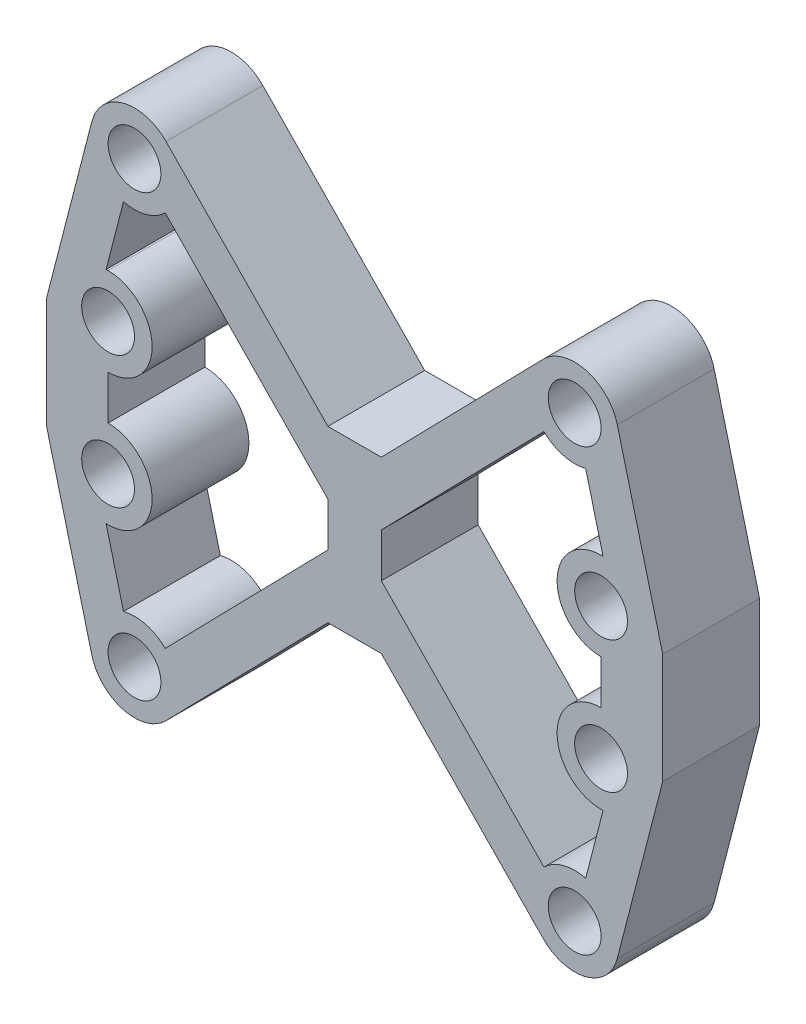
SolidWorks part; units mm, degrees
ref_plane "Front Plane" through (0, 0, 0) normal (0, 0, 1) x (1, 0, 0)
ref_plane "Top Plane" through (0, 0, 0) normal (0, 1, 0) x (1, 0, 0)
ref_plane "Right Plane" through (0, 0, 0) normal (1, 0, 0) x (0, 0, -1)
sketch "Sketch1" plane through (0, 0, 0) normal (0, 0, 1) x (1, 0, 0)
  line L0 (-5.2387, -9.525) -> (-13.6031, -18.0929)
  line L1 (-5.2387, 9.525) -> (5.2387, 9.525)
  line L2 (-22.225, 3.9688) -> (-22.225, -3.9688)
  line L3 (-5.2387, -9.525) -> (5.2387, -9.525)
  line L5 (-5.2387, 9.525) -> (-13.6031, 18.0929)
  line L8 (-22.225, 3.9688) -> (-18.9494, 16.668)
  line L9 (5.2387, -9.525) -> (13.6031, -18.0929)
  line L10 (-22.225, -3.9688) -> (-18.9494, -16.668)
  line L13 (5.2387, 9.525) -> (13.6031, 18.0929)
  line L14 (18.9494, 16.668) -> (22.225, 3.9688)
  line L15 (22.225, 3.9688) -> (22.225, -3.9687)
  line L16 (22.225, -3.9687) -> (18.9494, -16.668)
  arc A0 (-18.9494, -16.668) -> (-13.6031, -18.0929) centre (-15.875, -15.875) ccw
  arc A1 (-13.6031, 18.0929) -> (-18.9494, 16.668) centre (-15.875, 15.875) ccw
  arc A2 (13.6031, -18.0929) -> (18.9494, -16.668) centre (15.875, -15.875) ccw
  arc A3 (18.9494, 16.668) -> (13.6031, 18.0929) centre (15.875, 15.875) ccw
  point P2 (-22.225, 0)
  point P8 (0, -9.525)
  point P23 (0, 9.525)
  dimension "D1" = 6.35
  dimension "D2" = 44.45
  dimension "D3" = 15.875
  dimension "D4" = 10.4775
  dimension "D5" = 9.525
  dimension "D6" = 9.525
  dimension "D7" = 15.875
  dimension "D8" = 7.9375
extrude "Boss-Extrude1" add sketch "Sketch1" along normal blind 6.985
sketch "Sketch3" plane through (0, 0, 6.985) normal (0, 0, 1) x (1, 0, 0)
  line L1 (-18.9494, 16.668) -> (-22.225, 3.9688) construction
  line L2 (-22.225, 3.9688) -> (-22.225, -3.9688) construction
  line L3 (-1.9269, 6.1326) -> (1.9269, 6.1326)
  line L4 (-17.9224, 7.9375) -> (-16.668, 12.8006)
  line L9 (0, 9.525) -> (0, -9.525) construction
  line L11 (5.2387, 9.525) -> (-5.2387, 9.525) construction
  line L12 (-5.2387, -9.525) -> (5.2387, -9.525) construction
  line L13 (-22.225, 0) -> (22.225, 0) construction
  line L14 (22.225, -3.9687) -> (22.225, 3.9688) construction
  line L47 (-17.9224, 7.9375) -> (-17.78, 7.9375)
  line L57 (-1.9269, 1.5875) -> (-1.9269, -1.5875)
  line L58 (-17.78, 1.5875) -> (-17.78, -1.5875)
  line L60 (-17.9224, -7.9375) -> (-17.78, -7.9375)
  line L62 (-17.9224, -7.9375) -> (-16.668, -12.8006)
  line L63 (-13.6571, 13.6031) -> (-1.9269, 1.5875)
  line L64 (-13.6571, -13.6031) -> (-1.9269, -1.5875)
  line L65 (-5.2387, 9.525) -> (-13.6031, 18.0929) construction
  line L66 (17.9224, -7.9375) -> (16.668, -12.8006)
  line L67 (17.9224, -7.9375) -> (17.78, -7.9375)
  line L68 (17.78, 1.5875) -> (17.78, -1.5875)
  line L69 (17.9224, 7.9375) -> (17.78, 7.9375)
  line L70 (17.9224, 7.9375) -> (16.668, 12.8006)
  line L71 (13.6571, 13.6031) -> (1.9269, 1.5875)
  line L72 (1.9269, 1.5875) -> (1.9269, -1.5875)
  line L73 (13.6571, -13.6031) -> (1.9269, -1.5875)
  line L74 (-5.2387, 9.525) -> (-1.9269, 6.1326)
  line L75 (-5.2387, 9.525) -> (5.2387, 9.525)
  line L80 (5.2387, 9.525) -> (1.9269, 6.1326)
  line L81 (-5.2387, -9.525) -> (5.2387, -9.525)
  line L82 (-5.2387, -9.525) -> (-1.9269, -6.1326)
  line L83 (-1.9269, -6.1326) -> (1.9269, -6.1326)
  line L84 (5.2387, -9.525) -> (1.9269, -6.1326)
  circle A0 centre (-15.875, 15.875) radius 1.905
  arc A8 (-16.668, 12.8006) -> (-13.6571, 13.6031) centre (-15.875, 15.875) ccw
  arc A13 (-13.6031, 18.0929) -> (-18.9494, 16.668) centre (-15.875, 15.875) ccw construction
  circle A16 centre (-17.78, 4.7625) radius 1.905
  circle A18 centre (17.78, 4.7625) radius 1.905
  circle A19 centre (17.78, -4.7625) radius 1.905
  circle A20 centre (-17.78, -4.7625) radius 1.905
  circle A24 centre (15.875, 15.875) radius 1.905
  circle A25 centre (15.875, -15.875) radius 1.905
  circle A26 centre (-15.875, -15.875) radius 1.905
  arc A27 (-17.78, 1.5875) -> (-17.78, 7.9375) centre (-17.78, 4.7625) ccw
  arc A29 (-17.78, -1.5875) -> (-17.78, -7.9375) centre (-17.78, -4.7625) cw
  arc A30 (-16.668, -12.8006) -> (-13.6571, -13.6031) centre (-15.875, -15.875) cw
  arc A31 (16.668, -12.8006) -> (13.6571, -13.6031) centre (15.875, -15.875) ccw
  arc A32 (17.78, -1.5875) -> (17.78, -7.9375) centre (17.78, -4.7625) ccw
  arc A33 (17.78, 1.5875) -> (17.78, 7.9375) centre (17.78, 4.7625) cw
  arc A34 (16.668, 12.8006) -> (13.6571, 13.6031) centre (15.875, 15.875) cw
  point P59 (0, 0)
  point P60 (-1.9269, 0)
  point P62 (-17.78, 0)
  point P64 (0, 6.1326)
  dimension "D1" = 3.81
  dimension "D2" = 3.175
  dimension "D4" = 3.81
  dimension "D3" = 3.175
  dimension "D5" = 4.445
  dimension "D6" = 4.7625
extrude "Cut-Extrude1" cut sketch "Sketch3" against normal through all
fillet "Fillet2" [suppressed] radius 1.27
